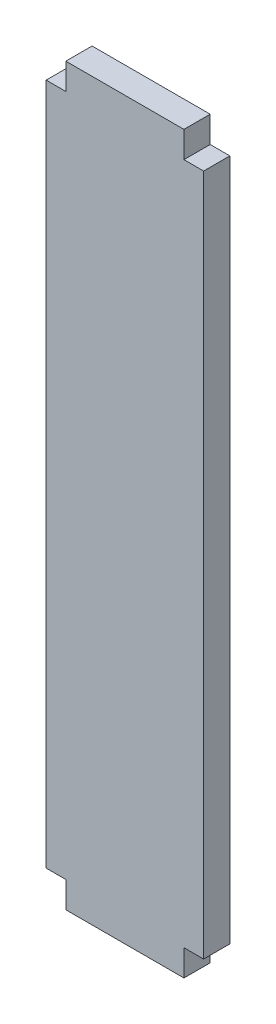
SolidWorks part; units mm, degrees
ref_plane "前视基准面" through (0, 0, 0) normal (0, 0, 1) x (1, 0, 0)
ref_plane "上视基准面" through (0, 0, 0) normal (0, 1, 0) x (1, 0, 0)
ref_plane "右视基准面" through (0, 0, 0) normal (1, 0, 0) x (0, 0, -1)
other "Configuration Table"
sketch "草图1" plane through (0, 0, 0) normal (0, 0, 1) x (1, 0, 0)
  line L0 (2314.8804, 1090.4105) -> (2314.8804, 1088.4105)
  line L1 (2323.8804, 1090.4105) -> (2323.8804, 1088.4105)
  line L2 (2314.8804, 1088.4105) -> (2313.3804, 1088.4105)
  line L3 (2323.8804, 1088.4105) -> (2325.3804, 1088.4105)
  line L4 (2313.3804, 1036.4105) -> (2313.3804, 1088.4105)
  line L5 (2314.8804, 1034.4105) -> (2314.8804, 1036.4105)
  line L6 (2323.8804, 1034.4105) -> (2323.8804, 1036.4105)
  line L7 (2314.8804, 1036.4105) -> (2313.3804, 1036.4105)
  line L8 (2323.8804, 1036.4105) -> (2325.3804, 1036.4105)
  line L9 (2314.8804, 1034.4105) -> (2323.8804, 1034.4105)
  line L10 (2314.8804, 1090.4105) -> (2323.8804, 1090.4105)
  line L11 (2325.3804, 1088.4105) -> (2325.3804, 1036.4105)
extrude "凸台-拉伸1" add sketch "草图1" along normal blind 2
